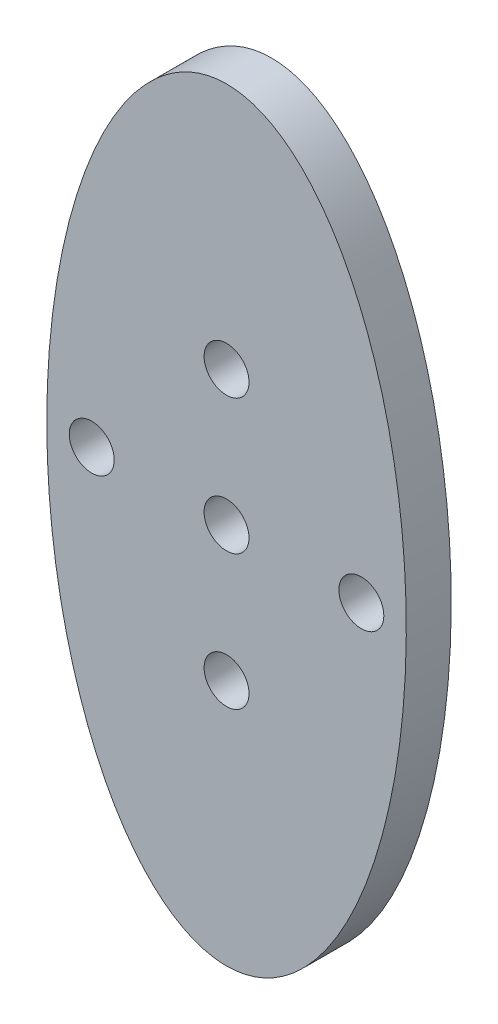
SolidWorks part; units mm, degrees
ref_plane "Alzado" through (0, 0, 0) normal (0, 0, 1) x (1, 0, 0)
ref_plane "Planta" through (0, 0, 0) normal (0, 1, 0) x (1, 0, 0)
ref_plane "Vista lateral" through (0, 0, 0) normal (1, 0, 0) x (0, 0, -1)
sketch "Model" plane through (0, 0, 0) normal (0, 0, 1) x (1, 0, 0)
  circle A0 centre (299.5188, 276.8788) radius 1.5
  circle A1 centre (299.5188, 294.8788) radius 1.5
  circle A2 centre (308.5188, 285.8788) radius 1.5
  circle A3 centre (290.5188, 285.8788) radius 1.5
  circle A4 centre (299.5188, 285.8788) radius 1.5
  ellipse E0 centre (299.5188, 285.8788) end of major axis (299.5188, 260.3788) minor radius 12
extrude "Saliente-Extruir1" add sketch "Model" along normal blind 3
